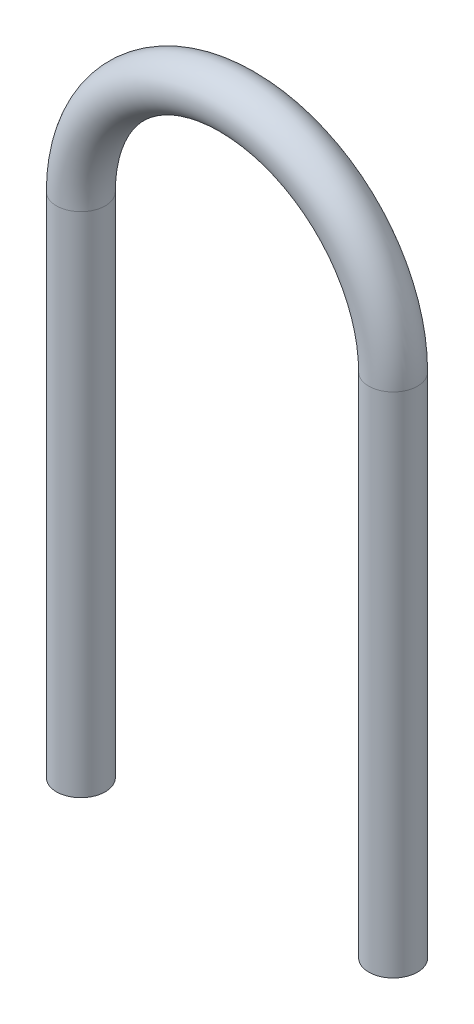
SolidWorks part; units mm, degrees
ref_plane "Plan de face" through (0, 0, 0) normal (0, 0, 1) x (1, 0, 0)
ref_plane "Plan de dessus" through (0, 0, 0) normal (0, 1, 0) x (1, 0, 0)
ref_plane "Plan de droite" through (0, 0, 0) normal (1, 0, 0) x (0, 0, -1)
sketch "Esquisse1" plane through (0, 0, 0) normal (0, 0, 1) x (1, 0, 0)
  line L0 (-25.4, 0) -> (-25.4, -82.55)
  line L1 (25.4, 0) -> (25.4, -82.55)
  arc A0 (25.4, 0) -> (-25.4, 0) centre (0, 0) ccw
  point P4 (0, 25.4)
  dimension "D1" = 50.8
  dimension "D2" = 107.95
ref_plane "Plan1" through (0, -82.55, 0) normal (0, 1, 0) x (-1, 0, 0)
sketch "Esquisse4" plane through (0, -82.55, 0) normal (0, 1, 0) x (-1, 0, 0)
  circle A0 centre (-25.4, 0) radius 3.9688
  dimension "D1" = 7.9375
sweep "Balayage1" add profiles "Esquisse4" path "Esquisse1"
